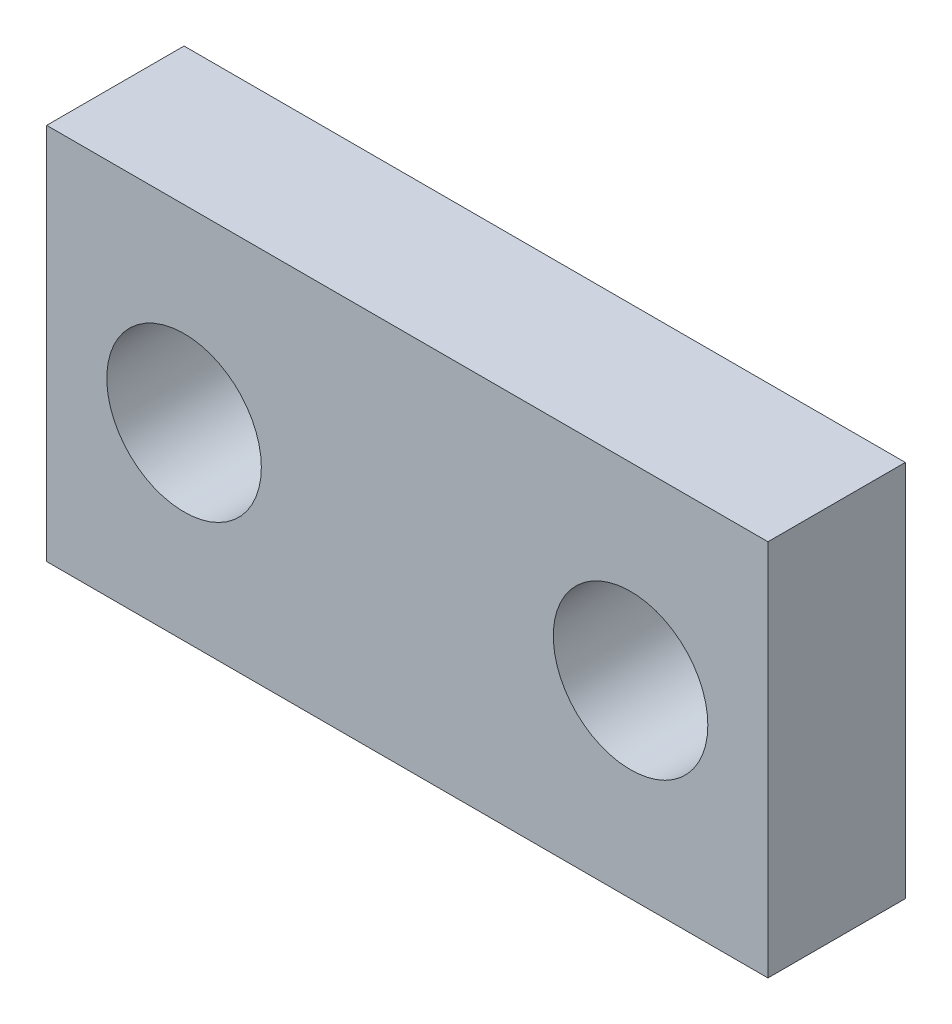
SolidWorks part; units mm, degrees
material "Printed PLA"
ref_plane "Front Plane" through (0, 0, 0) normal (0, 0, 1) x (1, 0, 0)
ref_plane "Top Plane" through (0, 0, 0) normal (0, 1, 0) x (1, 0, 0)
ref_plane "Right Plane" through (0, 0, 0) normal (1, 0, 0) x (0, 0, -1)
sketch "Sketch1" plane through (0, 0, 0) normal (0, 0, 1) x (1, 0, 0)
  line L0 (6.5, 0) -> (-6.5, 0) construction
  line L1 (10.5, 5.5) -> (-10.5, -5.5) construction
  line L2 (-10.5, 5.5) -> (10.5, 5.5)
  line L3 (-10.5, 5.5) -> (-10.5, -5.5)
  line L4 (-10.5, -5.5) -> (10.5, -5.5)
  line L5 (10.5, 5.5) -> (10.5, -5.5)
  circle A0 centre (-6.5, 0) radius 2.25
  circle A1 centre (6.5, 0) radius 2.25
  dimension "D1" = 4.5
  dimension "D2" = 13
  dimension "D3" = 11
  dimension "D4" = 21
extrude "Boss-Extrude1" add sketch "Sketch1" along normal blind 4
